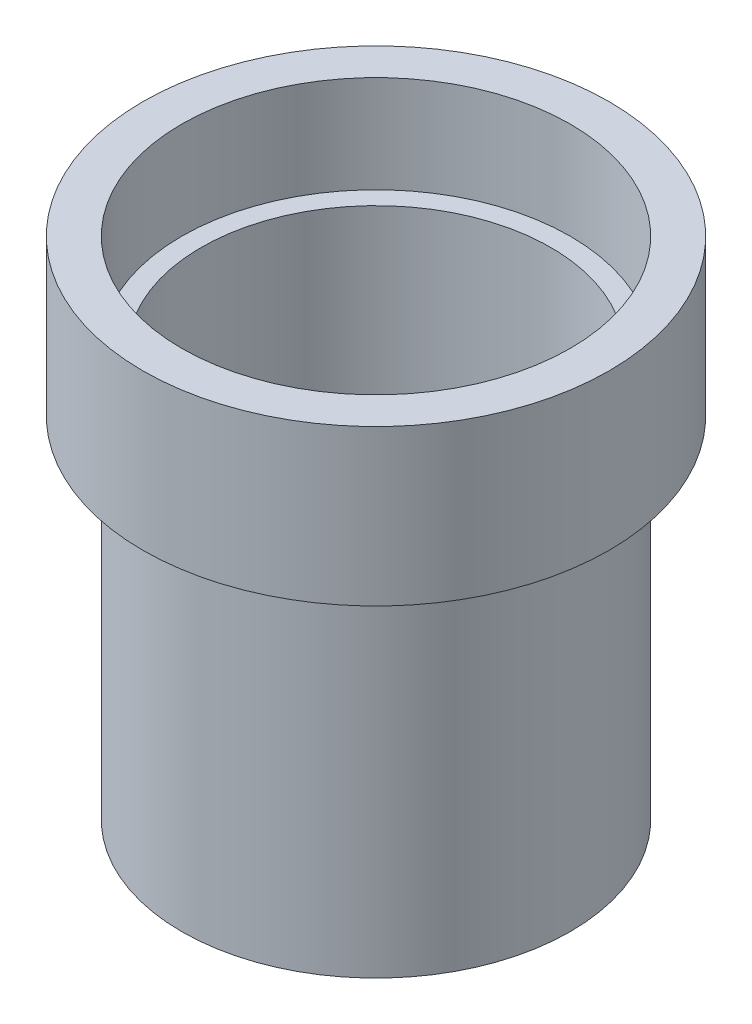
SolidWorks part; units mm, degrees
ref_plane "Plan de face" through (0, 0, 0) normal (0, 0, 1) x (1, 0, 0)
ref_plane "Plan de dessus" through (0, 0, 0) normal (0, 1, 0) x (1, 0, 0)
ref_plane "Plan de droite" through (0, 0, 0) normal (1, 0, 0) x (0, 0, -1)
sketch "Esquisse1" plane through (0, 0, 0) normal (0, 1, 0) x (1, 0, 0)
  circle A0 centre (0, 0) radius 4.5
  circle A1 centre (0, 0) radius 5
  dimension "D1" = 10
  dimension "D2" = 9
extrude "Boss.-Extru.1" add sketch "Esquisse1" along normal blind 9
sketch "Esquisse2" plane through (0, 9, 0) normal (0, 1, 0) x (1, 0, 0)
  circle A0 centre (0, 0) radius 6
  circle A1 centre (0, 0) radius 5
  circle A2 centre (0, 0) radius 5
  circle A3 centre (0, 0) radius 4.5 construction
  circle A4 centre (0, 0) radius 4.5
  circle M3 centre (0, 0) radius 5
  circle M4 centre (0, 0) radius 4.5
  dimension "D2" = 12
  dimension "D1" = 0
extrude "Boss.-Extru.2" add sketch "Esquisse2" along normal blind 1.5 contours A0 M3 | M3 M4
sketch "Esquisse3" plane through (0, 10.5, 0) normal (0, 1, 0) x (1, 0, 0)
  circle A0 centre (0, 0) radius 5
  circle A1 centre (0, 0) radius 6
  circle A2 centre (0, 0) radius 6
  dimension "D2" = 10
  dimension "D1" = 0
extrude "Boss.-Extru.3" add sketch "Esquisse3" along normal blind 2.5
